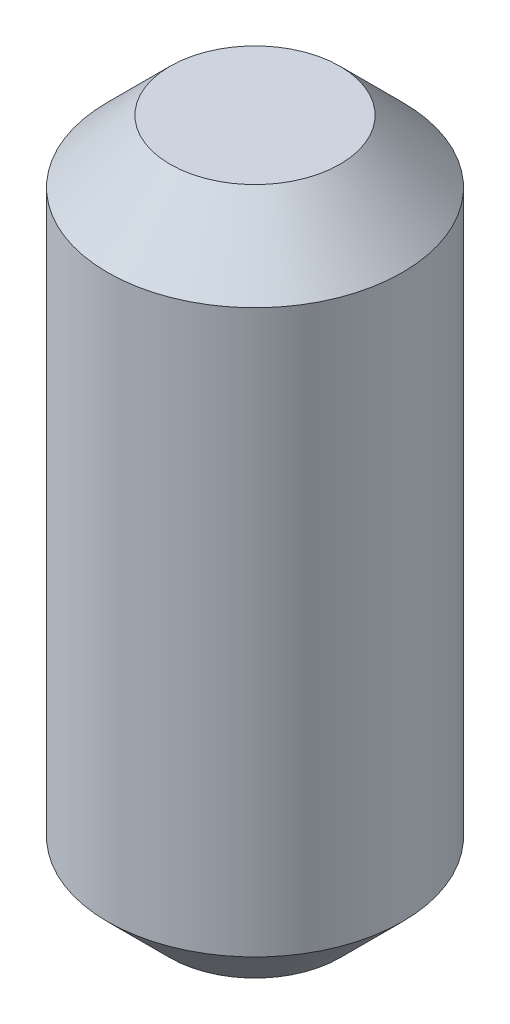
SolidWorks part; units mm, degrees
ref_plane "Front Plane" through (0, 0, 0) normal (0, 0, 1) x (1, 0, 0)
ref_plane "Top Plane" through (0, 0, 0) normal (0, 1, 0) x (1, 0, 0)
ref_plane "Right Plane" through (0, 0, 0) normal (1, 0, 0) x (0, 0, -1)
sketch "Sketch2" plane through (0, 0, 0) normal (0, 1, 0) x (1, 0, 0)
  circle A0 centre (0, 0) radius 2.9972
  dimension "D1" = 5.9944
extrude "Boss-Extrude1" add sketch "Sketch2" along normal blind 13.97
chamfer "Chamfer1" distance 1.27 angle 45 2 edges at (0, 13.97, 2.9972) (0, 0, 2.9972)
